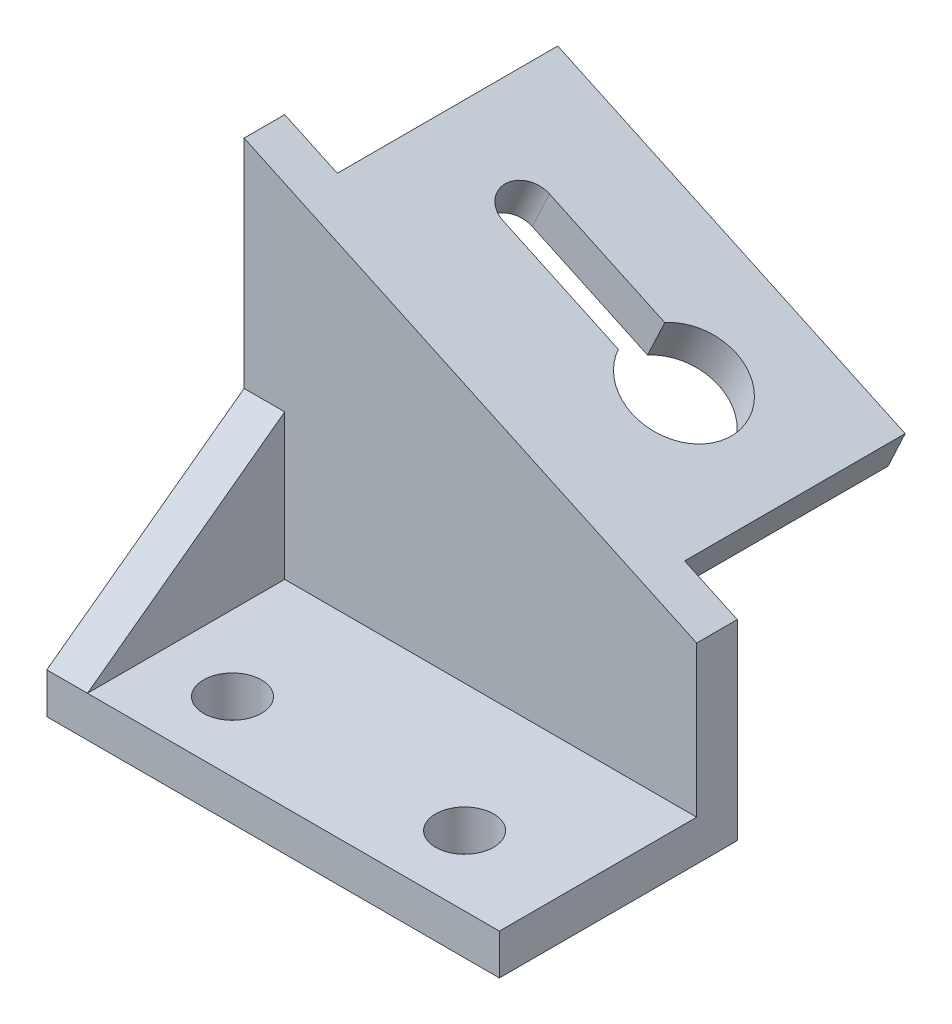
SolidWorks part; units mm, degrees
ref_plane "Płaszczyzna przednia" through (0, 0, 0) normal (0, 0, 1) x (1, 0, 0)
ref_plane "Płaszczyzna górna" through (0, 0, 0) normal (0, 1, 0) x (1, 0, 0)
ref_plane "Płaszczyzna prawa" through (0, 0, 0) normal (1, 0, 0) x (0, 0, -1)
sketch "Szkic1" plane through (0, 0, 0) normal (0, 1, 0) x (1, 0, 0)
  line L1 (0, 0) -> (78, 0)
  line L2 (0, 0) -> (0, 41)
  line L3 (0, 41) -> (78, 41)
  line L4 (78, 0) -> (78, 41)
  dimension "D1" = 78
  dimension "D2" = 41
extrude "Dodanie-wyciągnięcie1" add sketch "Szkic1" along normal blind 7 contours L2 L1 L4 L3
sketch "Szkic3" plane through (0, 0, -41) normal (0, 0, -1) x (-1, 0, 0)
  line L0 (-78, 7) -> (-78, 33)
  line L1 (-78, 33) -> (0, 69.372)
  line L2 (0, 69.372) -> (0, 7)
  line L3 (0, 7) -> (-78, 7)
  line L4 (0, 0) -> (-78, 0) construction
  dimension "D1" = 33
  dimension "D2" = 25
extrude "Dodanie-wyciągnięcie2" add sketch "Szkic3" against normal blind 7
sketch "Szkic4" plane through (0, 0, 0) normal (-1, 0, 0) x (0, 0, 1)
  line L0 (-34, 7) -> (-34, 32)
  line L1 (-34, 7) -> (-34, 69.372) construction
  line L2 (-34, 32) -> (0, 7)
  line L3 (0, 7) -> (-34, 7)
  dimension "D1" = 25
extrude "Dodanie-wyciągnięcie3" add sketch "Szkic4" against normal blind 7
sketch "Szkic5" plane through (0, 7, 0) normal (0, 1, 0) x (1, 0, 0)
  circle A0 centre (20, 12) radius 5
  circle A1 centre (60, 12) radius 5
  point P4 (0, 0)
  point P6 (0, 0)
  point P8 (0, 0)
  point P9 (0, 0)
  point P10 (-72.787, 34.594)
  point P11 (20.9975, 11.6576)
  dimension "D1" = 10
  dimension "D2" = 10
  dimension "D3" = 20
  dimension "D4" = 12
  dimension "D5" = 40
extrude "Wytnij-wyciągnięcie1" cut sketch "Szkic5" against normal blind 7
sketch "Szkic6" plane through (0, 0, -41) normal (0, 0, -1) x (-1, 0, 0)
  line L0 (-68.9369, 37.2262) -> (-65.9786, 30.882)
  line L1 (0, 69.372) -> (-78, 33) construction
  line L2 (-65.9786, 30.882) -> (-6.1048, 58.8017)
  line L3 (-6.1048, 58.8017) -> (-9.0631, 65.1458)
  line L4 (-9.0631, 65.1458) -> (-68.9369, 37.2262)
  dimension "D1" = 10
  dimension "D2" = 7
  dimension "D3" = 10
extrude "Dodanie-wyciągnięcie4" add sketch "Szkic6" along normal blind 38
sketch "Szkic7" plane through (26.571, 56.9817, 0) normal (0.4226, 0.9063, 0) x (0.9063, -0.4226, 0)
  line L0 (46.7456, 79) -> (46.7456, 41) construction
  line L1 (-19.3179, 79) -> (46.7456, 79) construction
  line L2 (-3.2544, 63) -> (18.6833, 63)
  line L3 (-3.2544, 55) -> (18.6833, 55)
  arc A1 (18.6833, 55) -> (18.6833, 63) centre (26.7456, 59) ccw
  arc A2 (-3.2544, 63) -> (-3.2544, 55) centre (-3.2544, 59) ccw
  dimension "D3" = 18
  dimension "D5" = 8
  dimension "D1" = 20
  dimension "D2" = 20
  dimension "D4" = 30
extrude "Wytnij-wyciągnięcie2" cut sketch "Szkic7" against normal blind 38
